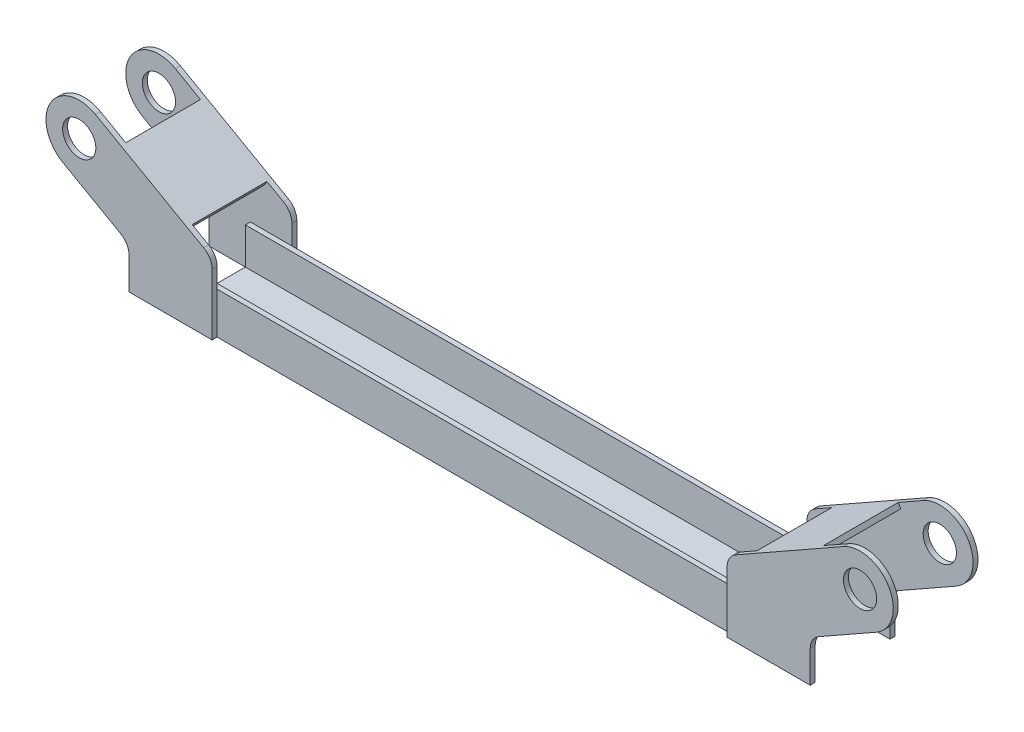
SolidWorks part; units mm, degrees
ref_plane "정면" through (0, 0, 0) normal (0, 0, 1) x (1, 0, 0)
ref_plane "윗면" through (0, 0, 0) normal (0, 1, 0) x (1, 0, 0)
ref_plane "우측면" through (0, 0, 0) normal (1, 0, 0) x (0, 0, -1)
sketch "스케치1" plane through (0, 0, 0) normal (1, 0, 0) x (0, 0, -1)
  line L0 (22.5, 0) -> (22.5, 25)
  line L1 (22.5, 25) -> (19.5, 25)
  line L2 (19.5, 25) -> (19.5, 3)
  line L3 (19.5, 3) -> (-19.5, 3)
  line L4 (-19.5, 3) -> (-19.5, 25)
  line L5 (-19.5, 25) -> (-22.5, 25)
  line L6 (-22.5, 25) -> (-22.5, 0)
  line L7 (-22.5, 0) -> (22.5, 0)
  point P5 (0, 0)
  dimension "D1" = 3
  dimension "D2" = 3
  dimension "D3" = 3
  dimension "D4" = 45
  dimension "D5" = 25
extrude "보스-돌출1" add sketch "스케치1" along normal mid plane 360
sketch "스케치2" plane through (0, 0, 22.5) normal (0, 0, 1) x (1, 0, 0)
  line L0 (155, 0) -> (155, 36.8076)
  line L1 (180, 0) -> (-180, 0) construction
  line L2 (160.0679, 45.5067) -> (225.1358, 82.3982)
  line L3 (225.1358, 82.3982) -> (244.8642, 47.6018) construction
  line L4 (244.8642, 47.6018) -> (210.0679, 27.8733)
  line L5 (205, 19.1742) -> (205, 0)
  line L6 (205, 0) -> (155, 0)
  arc A0 (244.8642, 47.6018) -> (225.1358, 82.3982) centre (235, 65) ccw
  arc A1 (210.0679, 27.8733) -> (205, 19.1742) centre (215, 19.1742) ccw
  arc A2 (155, 36.8076) -> (160.0679, 45.5067) centre (165, 36.8076) cw
  circle A3 centre (235, 65) radius 10
  point P13 (205, 25)
  dimension "D7" = 10
  dimension "D8" = 20
  dimension "D1" = 155
  dimension "D2" = 50
  dimension "D3" = 40
  dimension "D4" = 65
  dimension "D5" = 30
  dimension "D6" = 25
extrude "보스-돌출2" add sketch "스케치2" along normal blind 3
mirror "대칭 복사1" about plane through (0, 0, 0) normal (0, 0, 1) of "보스-돌출2"
sketch "스케치4" plane through (0, 0, 0) normal (0, 0, 1) x (1, 0, 0)
  line L0 (170, 51.1379) -> (210, 73.8167)
  line L1 (225.1358, 82.3982) -> (160.0679, 45.5067) construction
  line L2 (210, 73.8167) -> (211.4796, 71.2069)
  line L3 (211.4796, 71.2069) -> (171.4796, 48.5281)
  line L4 (171.4796, 48.5281) -> (170, 51.1379)
  line L5 (155, 36.8076) -> (155, 0) construction
  dimension "D1" = 3
  dimension "D2" = 15
  dimension "D3" = 40
extrude "보스-돌출3" add sketch "스케치4" along normal mid plane 45
mirror "대칭 복사2" about plane through (0, 0, 0) normal (1, 0, 0) of "보스-돌출3", "대칭 복사1", "보스-돌출2"
